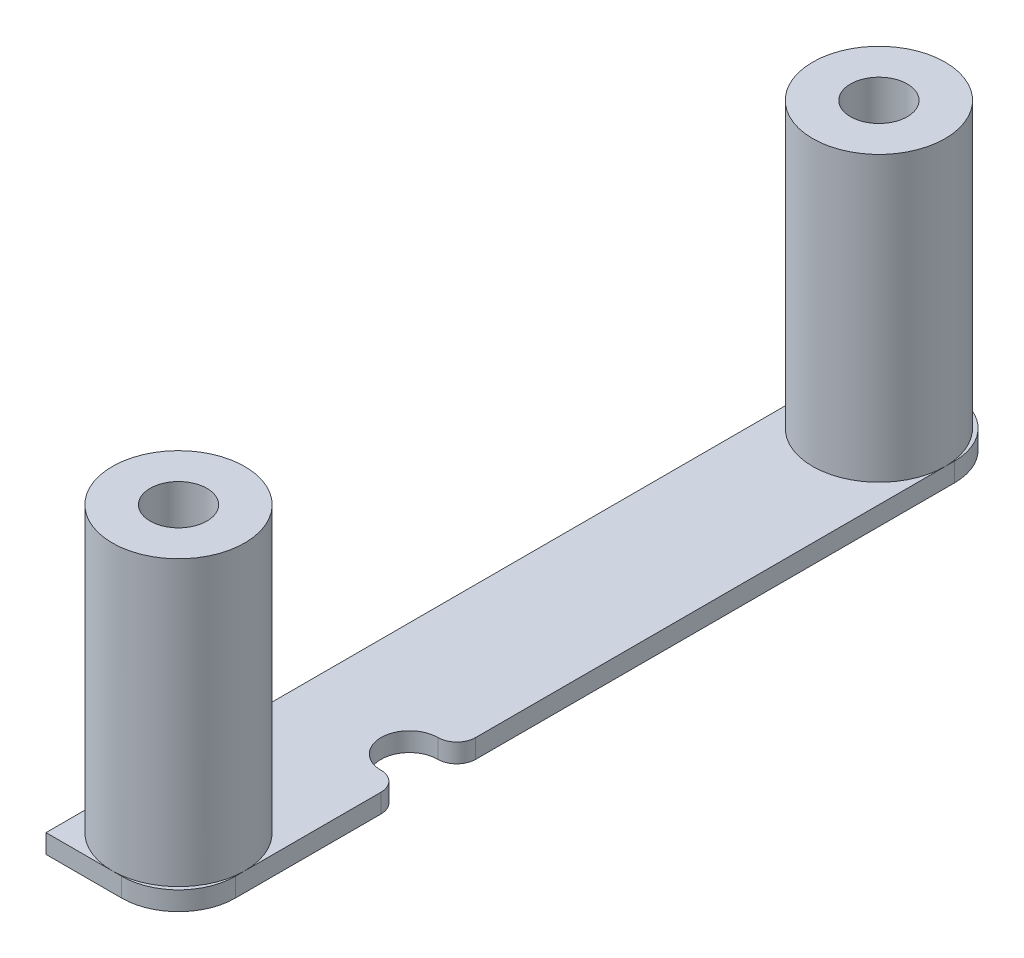
SolidWorks part; units mm, degrees
ref_plane "Front Plane" through (0, 0, 0) normal (0, 0, 1) x (1, 0, 0)
ref_plane "Top Plane" through (0, 0, 0) normal (0, 1, 0) x (1, 0, 0)
ref_plane "Right Plane" through (0, 0, 0) normal (1, 0, 0) x (0, 0, -1)
sketch "Sketch1" plane through (0, 0, 0) normal (0, 1, 0) x (1, 0, 0)
  line L1 (0, 0) -> (44, 0)
  line L2 (0, 0) -> (0, 44)
  line L3 (0, 44) -> (44, 44)
  line L4 (44, 0) -> (44, 44)
  dimension "D1" = 44
  dimension "D2" = 44
extrude "Boss-Extrude1" add sketch "Sketch1" along normal blind 1
sketch "Sketch2" plane through (0, 1, 0) normal (0, 1, 0) x (1, 0, 0)
  line L1 (0, 44) -> (0, 0) construction
  line L2 (44, 44) -> (0, 44) construction
  circle A0 centre (3.5, 40.5) radius 3.5
  circle A1 centre (40.5, 40.5) radius 3.5
  circle A2 centre (40.5, 3.5) radius 3.5
  circle A3 centre (3.5, 3.5) radius 3.5
  dimension "D1" = 7
  dimension "D2" = 37
  dimension "D3" = 37
  dimension "D4" = 37
extrude "Boss-Extrude2" add sketch "Sketch2" along normal blind 15
sketch "Sketch3" plane through (0, 16, 0) normal (0, 1, 0) x (1, 0, 0)
  circle A0 centre (3.5, 40.5) radius 1.5
  circle A1 centre (40.5, 40.5) radius 1.5
  circle A2 centre (40.5, 3.5) radius 1.5
  circle A3 centre (3.5, 3.5) radius 1.5
  dimension "D1" = 3
extrude "Cut-Extrude1" cut sketch "Sketch3" against normal blind 15
sketch "Sketch4" plane through (0, 1, 0) normal (0, 1, 0) x (1, 0, 0)
  line L6 (40.5, 0) -> (44, 0) construction
  line L7 (44, 0) -> (7, 0)
  line L8 (44, 0) -> (44, 44)
  line L9 (44, 44) -> (7, 44)
  line L10 (7, 0) -> (7, 44)
  line L11 (44, 0) -> (44, 3.5) construction
  dimension "D1" = 44
  dimension "D2" = 37
extrude "Cut-Extrude2" cut sketch "Sketch4" against normal through all both and the other way through all
sketch "Sketch5" plane through (0, 1, 0) normal (0, 1, 0) x (1, 0, 0)
  circle A0 centre (6, 13.2) radius 1.5
  dimension "D1" = 3
extrude "Cut-Extrude3" cut sketch "Sketch5" against normal blind 10
fillet "Fillet1" radius 3 2 edges at (7, 0.5, -44) (7, 0.5, 0)
fillet "Fillet2" radius 1 2 edges at (7, 0.5, -14.318) (7, 0.5, -12.082)
